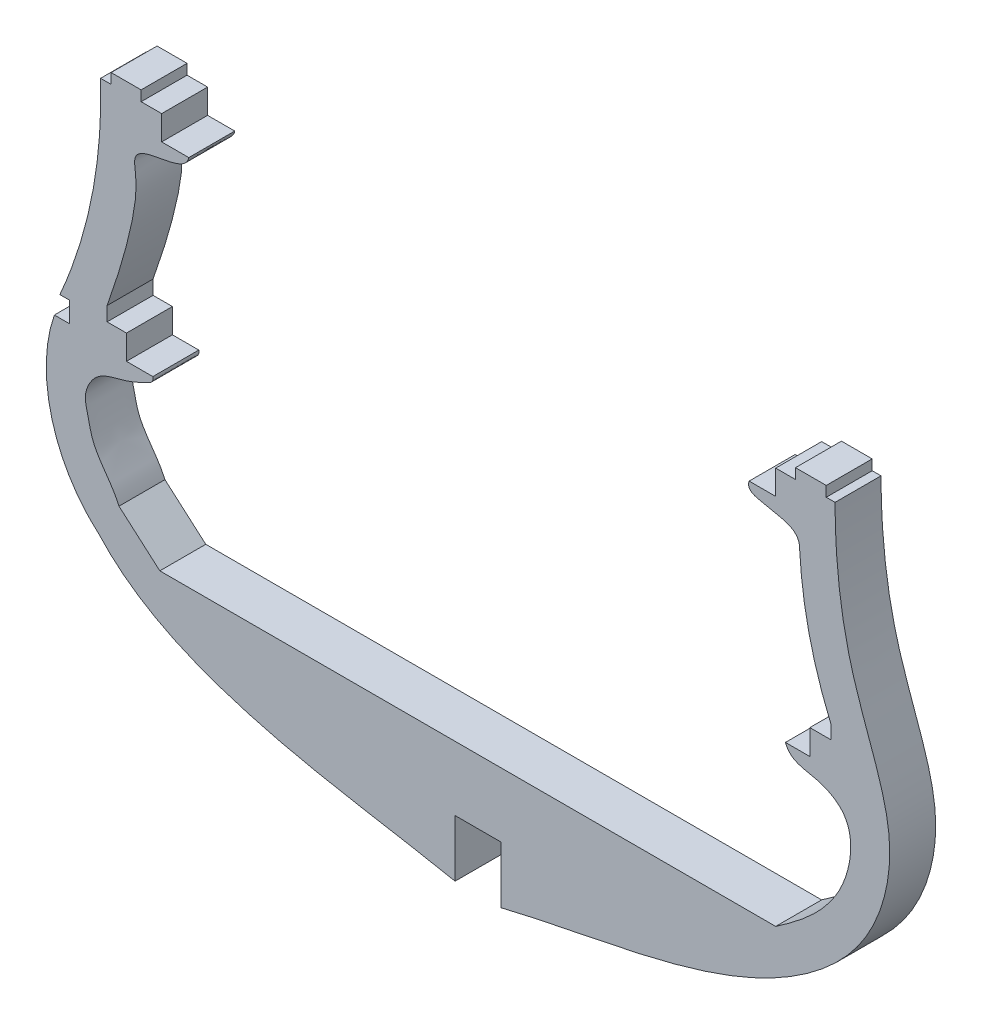
SolidWorks part; units mm, degrees
ref_plane "前视基准面" through (0, 0, 0) normal (0, 0, 1) x (1, 0, 0)
ref_plane "上视基准面" through (0, 0, 0) normal (0, 1, 0) x (1, 0, 0)
ref_plane "右视基准面" through (0, 0, 0) normal (1, 0, 0) x (0, 0, -1)
other "Configuration Table"
sketch "草图1" plane through (0, 0, 0) normal (0, 0, 1) x (1, 0, 0)
  line L0 (376.6667, 613.5) -> (1883.3333, 613.5) construction
  line L1 (1736.6312, 666.8355) -> (1843.8397, 666.8355)
  line L2 (1788.0278, 645.7447) -> (1788.0278, 655.6447)
  line L4 (1796.0281, 655.6447) -> (1796.0281, 645.7447)
  line L5 (1726.3134, 735.9282) -> (1728.1509, 735.9282)
  line L6 (1728.1509, 735.9282) -> (1728.1509, 737.7174)
  line L7 (1728.1509, 737.7174) -> (1733.3734, 737.7174)
  line L8 (1733.3734, 737.7174) -> (1733.3734, 735.9282)
  line L9 (1733.3734, 735.9282) -> (1736.9517, 735.9282)
  line L10 (1736.9517, 735.9282) -> (1736.9517, 731.6595)
  line L11 (1736.9517, 731.6595) -> (1741.6729, 731.6595)
  line L12 (1839.2135, 731.6595) -> (1843.8397, 731.6595)
  line L13 (1843.8397, 731.6595) -> (1843.8397, 735.9282)
  line L14 (1843.8397, 735.9282) -> (1847.2845, 735.9282)
  line L15 (1847.2845, 735.9282) -> (1847.2845, 737.7174)
  line L16 (1847.2845, 737.7174) -> (1852.6396, 737.7174)
  line L17 (1852.6396, 737.7174) -> (1852.6396, 735.9282)
  line L18 (1852.6396, 735.9282) -> (1854.1696, 735.9282)
  line L19 (1845.5355, 695.4222) -> (1849.7817, 695.4222)
  line L20 (1849.7817, 695.4222) -> (1849.7817, 699.7801)
  line L21 (1849.7817, 699.7801) -> (1853.488, 699.7801)
  line L22 (1853.488, 699.7801) -> (1853.488, 702.0585)
  line L23 (1719.2322, 699.7801) -> (1720.9415, 699.7801)
  line L24 (1720.9415, 699.7801) -> (1720.9415, 696.2254)
  line L25 (1720.9415, 696.2254) -> (1718.2733, 696.2254)
  line L26 (1727.4543, 702.2386) -> (1727.4543, 699.7801)
  line L27 (1727.4543, 699.7801) -> (1730.8224, 699.7801)
  line L28 (1730.8224, 699.7801) -> (1730.8224, 695.5129)
  line L29 (1730.8224, 695.5129) -> (1735.4153, 695.5129)
  line L30 (1788.0278, 655.6447) -> (1796.0281, 655.6447)
  spline S0 degree 3 poles (1854.1696, 735.9282) (1854.1848, 728.0887) (1855.2514, 716.6265) (1860.6543, 701.8) (1865.2593, 688.6697) (1861.0505, 672.4798) (1838.8996, 651.9888) (1813.4731, 650.0608) (1796.0281, 645.7447) knots 0 0 0 0 0.175103 0.250263 0.350923 0.478483 0.593543 1 1 1 1
  spline S1 degree 2 poles (1726.3134, 735.9282) (1726.9032, 717.2257) (1719.2322, 699.7801) knots 0 0 0 1 1 1
  spline S2 degree 3 poles (1718.2733, 696.2254) (1714.7921, 686.2892) (1717.9001, 674.1568) (1725.8738, 667.2258) knots 0 0 0 0 1 1 1 1
  spline S3 degree 3 poles (1725.8738, 667.2258) (1731.6047, 660.8412) (1752.2842, 650.9615) (1774.4857, 648.486) (1788.0278, 645.7447) knots 0 0 0 0 0.379946 1 1 1 1
  spline S4 degree 3 poles (1727.4543, 702.2386) (1729.4493, 707.7955) (1733.0265, 719.144) (1732.3289, 725.139) (1731.622, 730.152) (1741.0172, 728.2819) (1741.6729, 731.6595) knots 0 0 0 0 0.48667 0.533234 0.61512 1 1 1 1
  spline S5 degree 1 poles (1736.6312, 666.8355) (1729.5211, 673.0267) knots 0 0 1 1
  spline S6 degree 3 poles (1735.4153, 695.5129) (1735.5956, 694.5694) (1734.4336, 694.1403) (1732.6322, 693.2092) (1729.8491, 692.1513) (1726.3555, 691.5771) (1724.2803, 689.0494) (1723.3603, 686.486) (1724.2134, 683.7946) (1725.0993, 678.8162) (1728.3279, 675.9005) (1729.5211, 673.0267) knots 0 0 0 0 0.06877 0.107167 0.201072 0.358564 0.431586 0.50956 0.612882 0.696964 1 1 1 1
  spline S7 degree 3 poles (1843.8397, 666.8355) (1849.0489, 670.401) (1856.6584, 676.4307) (1857.4325, 689.4979) (1850.9357, 693.1488) (1846.4351, 693.0068) (1845.5355, 695.4222) knots 0 0 0 0 0.482118 0.698636 0.830471 1 1 1 1
  spline S17 degree 3 poles (1839.2135, 731.6595) (1838.7241, 730.19) (1841.2546, 729.6529) (1844.6998, 728.9479) (1848.0165, 728.2771) (1847.9971, 725.9197) knots 0 0 0 0 0.293172 0.509747 1 1 1 1
  spline S18 degree 2 poles (1853.488, 702.0585) (1848.6326, 713.452) (1847.9971, 725.9197) knots 0 0 0 1 1 1
  dimension "D3" = 9.9
extrude "凸台-拉伸1" add sketch "草图1" along normal blind 8
